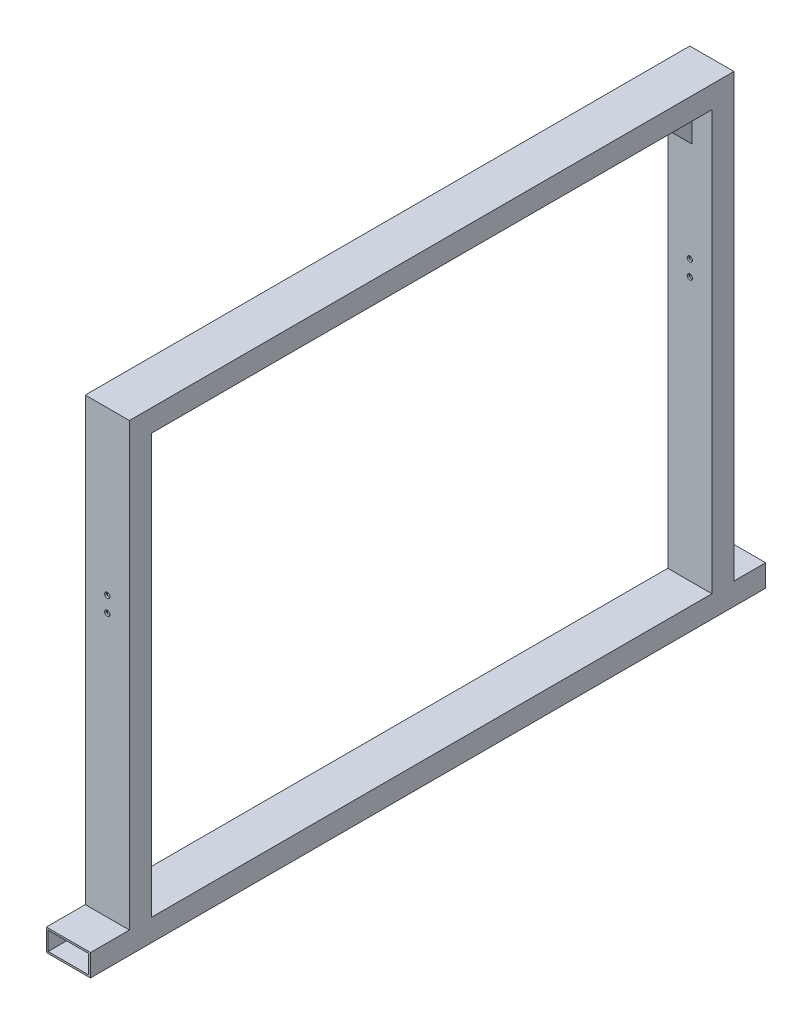
SolidWorks part; units mm, degrees
ref_plane "Front Plane" through (0, 0, 0) normal (0, 0, 1) x (1, 0, 0)
ref_plane "Top Plane" through (0, 0, 0) normal (0, 1, 0) x (1, 0, 0)
ref_plane "Right Plane" through (0, 0, 0) normal (1, 0, 0) x (0, 0, -1)
sketch "Sketch1" plane through (0, 0, 0) normal (0, 0, 1) x (1, 0, 0)
  line L0 (-23, 10.5) -> (23, 10.5)
  line L1 (-25, 12.5) -> (25, 12.5)
  line L2 (-25, 12.5) -> (-25, -12.5)
  line L3 (-25, -12.5) -> (25, -12.5)
  line L4 (25, 12.5) -> (25, -12.5)
  line L5 (-25, 12.5) -> (25, -12.5) construction
  line L6 (-25, -12.5) -> (25, 12.5) construction
  line L7 (23, 10.5) -> (23, -10.5)
  line L8 (-23, -10.5) -> (23, -10.5)
  line L9 (-23, 10.5) -> (-23, -10.5)
  point P0 (0, 0)
  point P5 (0, 0)
  dimension "D1" = 50
  dimension "D2" = 25
  dimension "D3" = 2
extrude "Boss-Extrude1" add sketch "Sketch1" along normal blind 765
sketch "Sketch2" plane through (0, 12.5, 0) normal (0, 1, 0) x (1, 0, 0)
  line L0 (0, 4.0816) -> (0, -760.9184) construction
  line L1 (0, -378.4184) -> (241.0697, -378.4184) construction
  line L2 (-258.7857, -708.4184) -> (0, -708.4184) construction
  line L3 (-258.7857, -378.4184) -> (0, -378.4184) construction
  line L4 (-23, -37.9184) -> (23, -37.9184)
  line L5 (23, -58.9184) -> (23, -37.9184)
  line L6 (-23, -58.9184) -> (23, -58.9184)
  line L7 (-23, -58.9184) -> (-23, -37.9184)
  line L8 (-25, -720.9184) -> (25, -695.9184) construction
  line L9 (-25, -695.9184) -> (25, -720.9184) construction
  line L10 (25, -695.9184) -> (25, -720.9184)
  line L11 (-25, -720.9184) -> (25, -720.9184)
  line L12 (-258.7857, -48.4184) -> (0, -48.4184) construction
  line L13 (-25, -695.9184) -> (-25, -720.9184)
  line L14 (-25, -60.9184) -> (25, -60.9184)
  line L15 (-25, -60.9184) -> (-25, -35.9184)
  line L16 (-25, -35.9184) -> (25, -35.9184)
  line L17 (25, -60.9184) -> (25, -35.9184)
  line L18 (-25, -60.9184) -> (25, -35.9184) construction
  line L19 (-25, -35.9184) -> (25, -60.9184) construction
  line L20 (-25, -695.9184) -> (25, -695.9184)
  line L21 (-23, -697.9184) -> (-23, -718.9184)
  line L22 (-23, -697.9184) -> (23, -697.9184)
  line L23 (23, -697.9184) -> (23, -718.9184)
  line L24 (-23, -718.9184) -> (23, -718.9184)
  dimension "D1" = 50
  dimension "D4" = 25
  dimension "D2" = 330
  dimension "D3" = 330
  dimension "D5" = 2
extrude "Boss-Extrude2" add sketch "Sketch2" along normal blind 500
sketch "Sketch3" plane through (0, 0, 720.9184) normal (0, 0, 1) x (1, 0, 0)
  line L1 (-75.2751, 512.5) -> (57.5641, 512.5) construction
  line L2 (-75.2751, 500) -> (57.5641, 500) construction
  line L3 (0, 500) -> (0, 462.642) construction
  line L4 (-23, 510.5) -> (23, 510.5)
  line L5 (-25, 487.5) -> (25, 487.5)
  line L6 (-25, 487.5) -> (-25, 512.5)
  line L7 (-25, 512.5) -> (25, 512.5)
  line L8 (25, 487.5) -> (25, 512.5)
  line L9 (-25, 487.5) -> (25, 512.5) construction
  line L10 (-25, 512.5) -> (25, 487.5) construction
  line L11 (23, 489.5) -> (23, 510.5)
  line L12 (-23, 489.5) -> (23, 489.5)
  line L13 (-23, 489.5) -> (-23, 510.5)
  dimension "D1" = 12.5
  dimension "D2" = 2
extrude "Boss-Extrude3" add sketch "Sketch3" against normal up to surface (685 mm away) up to face at (0, 262.5, 35.9184)
other "Gusset1" parameters "D1"=5, "D2"=5, "D3"=0, "D4"=0, "D10"=5, "D11"=45, "D12"=45, "D13"=15, "D14"=45, "D15"=15, "D16"=12.5, "D17"=12.5, "D18"=45
sketch "Sketch6" plane through (0, 487.5, 60.9184) normal (1, 0, 0) x (0, 0, -1)
  line L0 (0, 0) -> (-45, 0)
  line L1 (0, 0) -> (0, -45)
  line L2 (-45, 0) -> (0, -45)
other "Gusset2" parameters "D1"=5, "D2"=5, "D3"=0, "D4"=0, "D10"=5, "D11"=45, "D12"=45, "D13"=15, "D14"=45, "D15"=15
sketch "Sketch7" plane through (0, 487.5, 695.9184) normal (1, 0, 0) x (0, 0, -1)
  line L0 (0, 0) -> (0, -45)
  line L1 (0, 0) -> (45, 0)
  line L2 (0, -45) -> (45, 0)
sketch "Sketch9" plane through (0, 0, 695.9184) normal (0, 0, -1) x (-1, 0, 0)
  circle A1 centre (0, 310.8876) radius 3
  circle A2 centre (0, 310.8876) radius 3
  circle A3 centre (0, 328.5) radius 3
  circle A4 centre (0, 328.5) radius 3
  dimension "D1" = 0
  dimension "D2" = 0
extrude "Cut-Extrude1" cut sketch "Sketch9" against normal blind 70
sketch "Sketch10" plane through (0, 0, 60.9184) normal (0, 0, 1) x (1, 0, 0)
  circle A1 centre (0, 310.8876) radius 3
  circle A2 centre (0, 310.8876) radius 3
  circle A3 centre (0, 328.5) radius 3
  circle A4 centre (0, 328.5) radius 3
  dimension "D1" = 0
  dimension "D2" = 0
extrude "Cut-Extrude2" cut sketch "Sketch10" against normal blind 70
